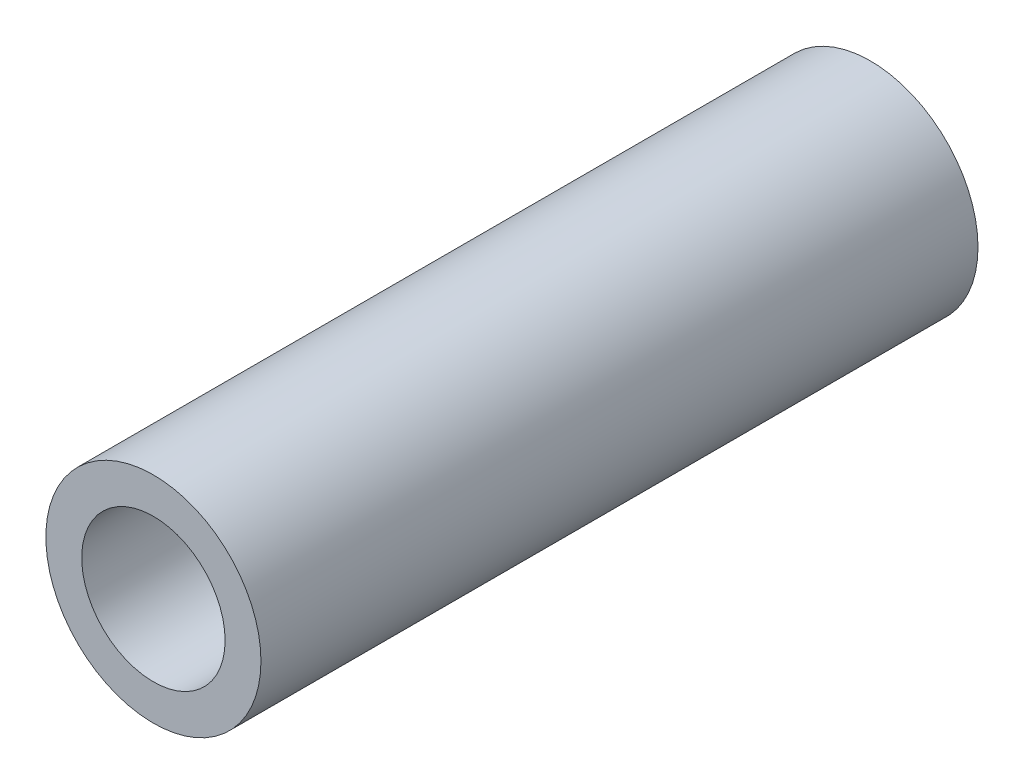
SolidWorks part; units mm, degrees
ref_plane "Front Plane" through (0, 0, 0) normal (0, 0, 1) x (1, 0, 0)
ref_plane "Top Plane" through (0, 0, 0) normal (0, 1, 0) x (1, 0, 0)
ref_plane "Right Plane" through (0, 0, 0) normal (1, 0, 0) x (0, 0, -1)
sketch "Sketch1" plane through (0, 0, 0) normal (0, 0, 1) x (1, 0, 0)
  circle A0 centre (0, 0) radius 3
  circle A1 centre (0, 0) radius 2
  dimension "D1" = 6
  dimension "D2" = 4
extrude "Boss-Extrude1" add sketch "Sketch1" along normal blind 20
